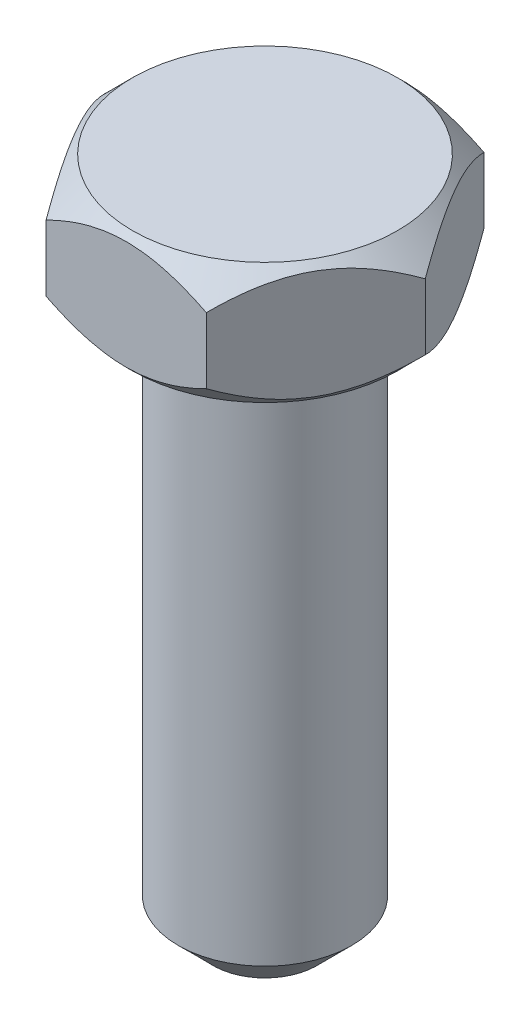
SolidWorks part; units mm, degrees
ref_plane "Спереди" through (0, 0, 0) normal (0, 0, 1) x (1, 0, 0)
ref_plane "Сверху" through (0, 0, 0) normal (0, 1, 0) x (1, 0, 0)
ref_plane "Справа" through (0, 0, 0) normal (1, 0, 0) x (0, 0, -1)
sketch "Эскиз1" plane through (0, 0, 0) normal (0, 1, 0) x (1, 0, 0)
  line L0 (-2.3094, 4) -> (2.3094, 4)
  line L1 (2.3094, 4) -> (4.6188, 0)
  line L2 (4.6188, 0) -> (2.3094, -4)
  line L3 (2.3094, -4) -> (-2.3094, -4)
  line L4 (-2.3094, -4) -> (-4.6188, 0)
  line L5 (-4.6188, 0) -> (-2.3094, 4)
  dimension "D5" = 4
  dimension "D2" = 120
  dimension "D3" = 120
  dimension "D4" = 120
  dimension "D6" = 4
  dimension "D7" = 4
  dimension "D8" = 4
  dimension "D9" = 4
  dimension "D10" = 120
  dimension "D11" = 4
extrude "Вытянуть1" add sketch "Эскиз1" against normal blind 3.5
sketch "Эскиз5" plane through (0, -3.5, 0) normal (0, -1, 0) x (1, 0, 0)
  circle A0 centre (0, 0) radius 2.5
  dimension "D1" = 5
extrude "Вытянуть2" add sketch "Эскиз5" along normal blind 16
chamfer "Фаска1" distance 1 angle 45 1 edges at (0, -19.5, -2.5)
ref_axis "Ось1" through (0, -3.5, 0) along (0, -1, 0)
ref_plane "Плоскость1" through (0, 0, 0) normal (0, 0, 1) x (1, 0, 0)
sketch "Эскиз4" plane through (0, 0, 0) normal (0, 0, 1) x (1, 0, 0)
  line L0 (-4.6188, -0.8) -> (-3.8188, 0)
  line L1 (-4.6188, -3.5) -> (-4.6188, 0) construction
  line L2 (-4.6188, 0) -> (-2.3094, 0) construction
  line L3 (-3.8188, 0) -> (-4.6188, 0)
  line L4 (-4.6188, 0) -> (-4.6188, -0.8)
  line L5 (-4.6188, -2.7) -> (-3.8188, -3.5)
  line L6 (-4.6188, -3.5) -> (-2.3094, -3.5) construction
  line L7 (-3.8188, -3.5) -> (-4.6188, -3.5)
  line L8 (-4.6188, -3.5) -> (-4.6188, -2.7)
  dimension "D1" = 0.8
  dimension "D2" = 0.8
  dimension "D3" = 0.8
  dimension "D4" = 0.8
revolve "Вырез-Повернуть1" cut sketch "Эскиз4" angle 360 about axis through (0, -3.5, 0) along (0, -1, 0)
